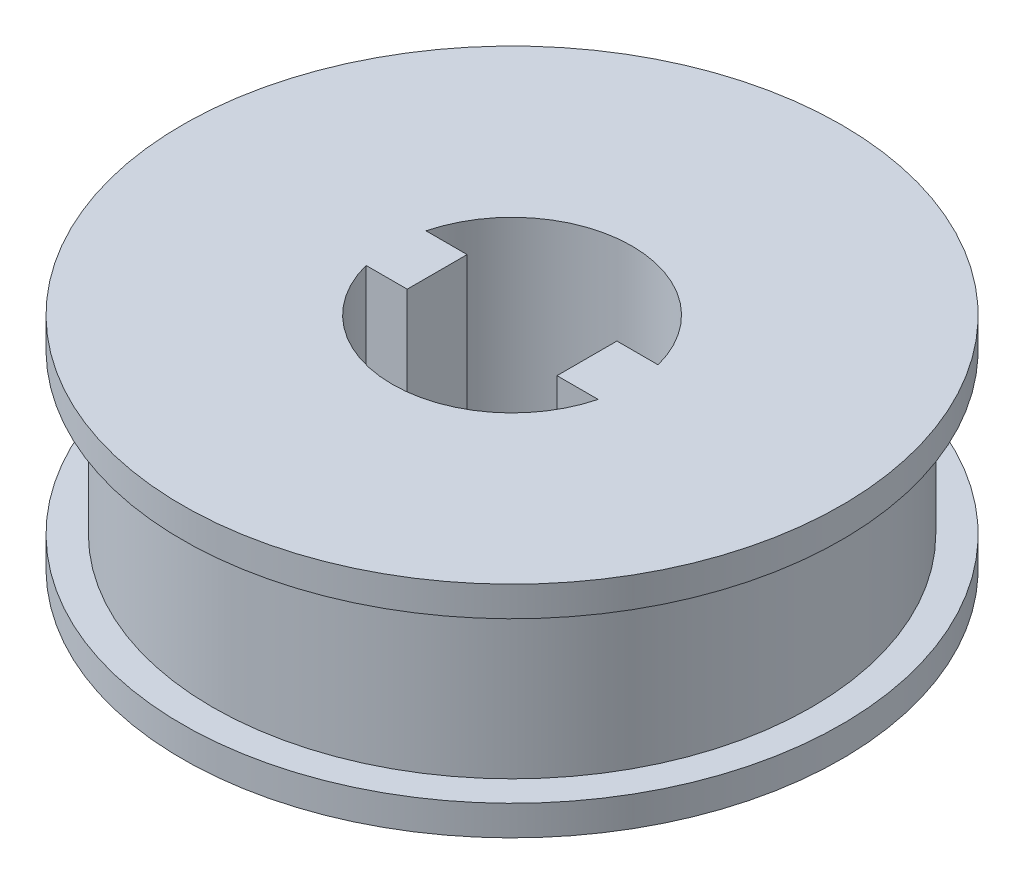
SolidWorks part; units mm, degrees
ref_plane "Plan de face" through (0, 0, 0) normal (0, 0, 1) x (1, 0, 0)
ref_plane "Plan de dessus" through (0, 0, 0) normal (0, 1, 0) x (1, 0, 0)
ref_plane "Plan de droite" through (0, 0, 0) normal (1, 0, 0) x (0, 0, -1)
sketch "Esquisse2" plane through (0, 0, 0) normal (0, 0, 1) x (1, 0, 0)
  line L0 (6, 5.3653) -> (6, -5.6347)
  line L1 (6, 5.3653) -> (16.5, 5.3653)
  line L2 (16.5, 5.3653) -> (16.5, 3.8653)
  line L3 (16.5, 3.8653) -> (15, 3.8653)
  line L4 (16.5, -5.6347) -> (6, -5.6347)
  line L5 (0, 0) -> (0, 15.5979) construction
  line L6 (15, 3.8653) -> (15, -4.1347)
  line L7 (15, -4.1347) -> (16.5, -4.1347)
  line L8 (16.5, -4.1347) -> (16.5, -5.6347)
  dimension "D1" = 6
  dimension "D2" = 1.5
  dimension "D3" = 11
  dimension "D4" = 16.5
  dimension "D5" = 1.5
  dimension "D6" = 8
  dimension "D7" = 1.5
  dimension "D8" = 1.5
  dimension "D9" = 15
revolve "Révolution1" add sketch "Esquisse2" angle 360 about L5
sketch "Esquisse6" plane through (0, 5.3653, 0) normal (0, 1, 0) x (1, 0, 0)
  line L0 (0, 0) -> (0, -8.5771) construction
  line L1 (-8.25, -1.5) -> (-3.75, -1.5)
  line L2 (-6, 0) -> (13.3406, 0) construction
  line L3 (-8.25, -1.5) -> (-8.25, 1.5)
  line L4 (-8.25, 1.5) -> (-3.75, 1.5)
  line L5 (-3.75, -1.5) -> (-3.75, 1.5)
  line L6 (-8.25, -1.5) -> (-3.75, 1.5) construction
  line L7 (-8.25, 1.5) -> (-3.75, -1.5) construction
  line L8 (8.25, -1.5) -> (3.75, 1.5) construction
  line L9 (3.75, -1.5) -> (3.75, 1.5)
  line L10 (8.25, 1.5) -> (3.75, 1.5)
  line L11 (8.25, 1.5) -> (3.75, -1.5) construction
  line L12 (8.25, -1.5) -> (8.25, 1.5)
  line L13 (8.25, -1.5) -> (3.75, -1.5)
  circle A0 centre (0, 0) radius 6 construction
  point P3 (-6, 0)
  point P17 (6, 0)
  dimension "D1" = 3
  dimension "D2" = 2.25
  dimension "D3" = 6
  dimension "D4" = 6
extrude "Boss.-Extru.1" add sketch "Esquisse6" against normal blind 11
